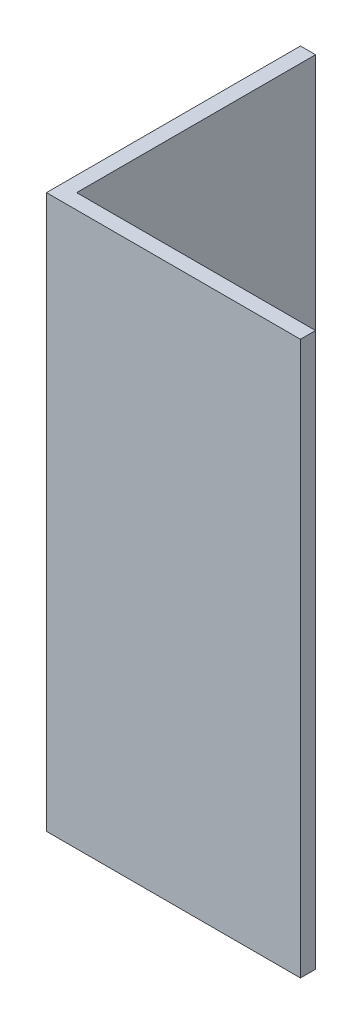
SolidWorks part; units mm, degrees
ref_plane "Front Plane" through (0, 0, 0) normal (0, 0, 1) x (1, 0, 0)
ref_plane "Top Plane" through (0, 0, 0) normal (0, 1, 0) x (1, 0, 0)
ref_plane "Right Plane" through (0, 0, 0) normal (1, 0, 0) x (0, 0, -1)
sketch "Sketch1" plane through (0, 0, 0) normal (0, 1, 0) x (1, 0, 0)
  line L0 (0, 47.5) -> (0, 0)
  line L1 (0, 0) -> (47.5, 0)
  line L2 (47.5, 0) -> (47.5, -3)
  line L3 (47.5, -3) -> (-3, -3)
  line L4 (-3, -3) -> (-3, 47.5)
  line L5 (-3, 47.5) -> (0, 47.5)
  line L6 (47.5, -1.5) -> (-1.5, -1.5) construction
  line L7 (-1.5, -1.5) -> (-1.5, 47.5) construction
  line L9 (-1.5, 0) -> (-50.5, 0) construction
  line L10 (-1.5, 0) -> (-1.5, -3) construction
  line L11 (-1.5, -3) -> (-50.5, -3) construction
  line L12 (-50.5, 0) -> (-50.5, -3) construction
  dimension "D1" = 3
  dimension "D2" = 49
  dimension "D3" = 49
extrude "Boss-Extrude1" add sketch "Sketch1" along normal blind 110
equation "\"D3@Sketch1\"=\"D2@Sketch1\""
